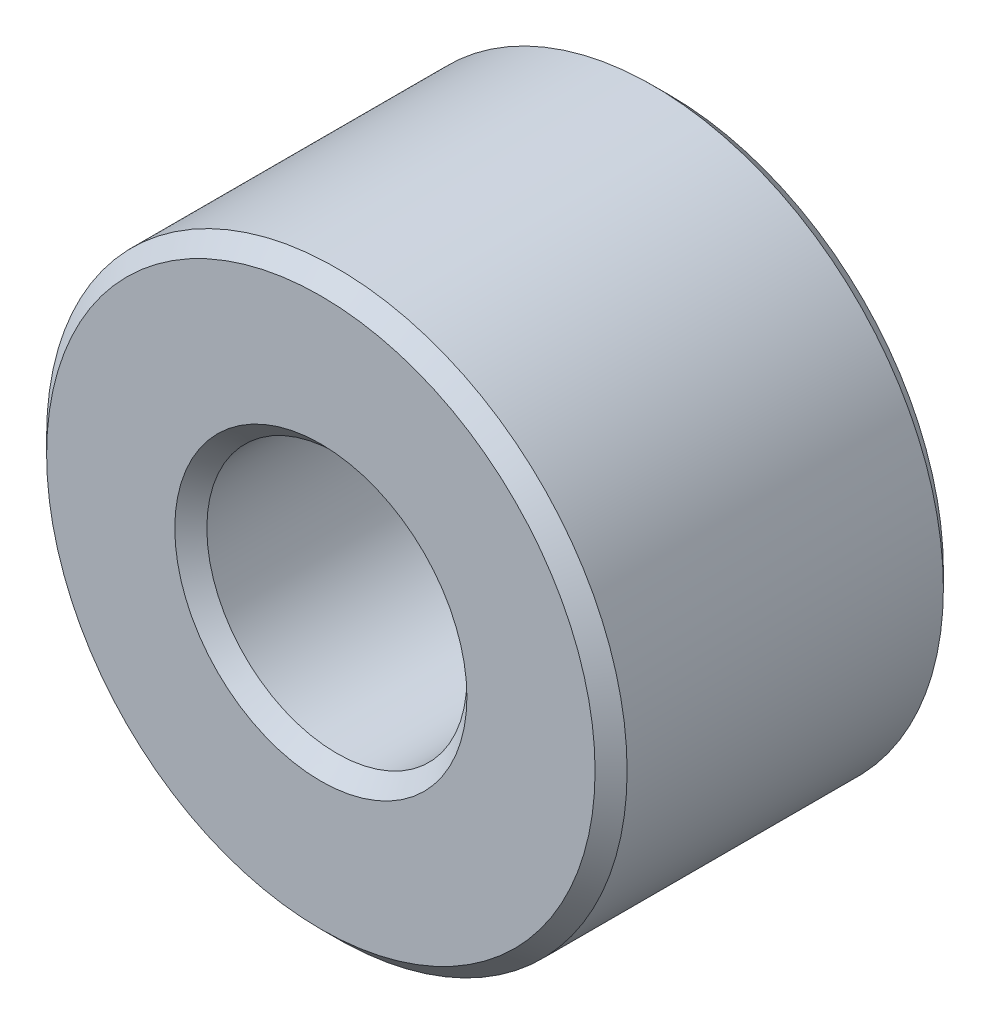
SolidWorks part; units mm, degrees
ref_plane "Front Plane" through (0, 0, 0) normal (0, 0, 1) x (1, 0, 0)
ref_plane "Top Plane" through (0, 0, 0) normal (0, 1, 0) x (1, 0, 0)
ref_plane "Right Plane" through (0, 0, 0) normal (1, 0, 0) x (0, 0, -1)
sketch "Sketch1" plane through (0, 0, 0) normal (0, 0, 1) x (1, 0, 0)
  circle A0 centre (0, 0) radius 3.9688 construction
  circle A1 centre (0, 0) radius 1.778 construction
  point P4 (0, 3.9688)
  dimension "ID" = 3.556
  dimension "OD" = 7.9375
sketch "Sketch2" plane through (0, 0, 0) normal (1, 0, 0) x (0, 0, -1)
  line L0 (-2.3813, 3.9688) -> (2.3813, 3.9688) construction
  dimension "Length" = 4.7625
sketch "Sketch3" plane through (0, 0, 0) normal (0, 0, 1) x (1, 0, 0)
  circle A0 centre (0, 0) radius 1.778 construction
  circle A1 centre (0, 0) radius 3.9688 construction
  circle A2 centre (0, 0) radius 1.778
  circle A3 centre (0, 0) radius 3.9688
extrude "Boss-Extrude1" add sketch "Sketch3" against normal up to vertex (2.3813 mm away) and the other way up to vertex (2.3813 mm away) up to point (0, 3.9688, -2.3813) other way up to point (0, 3.9688, 2.3813)
chamfer "Chamfer1" distance 0.2191 angle 45 4 edges at (3.9688, 0, 2.3813) (3.9688, 0, -2.3813) (1.778, 0, 2.3813) (1.778, 0, -2.3813)
equation "\"D1@Chamfer1\"=(\"OD@Sketch1\"-\"ID@Sketch1\")*0.05"
